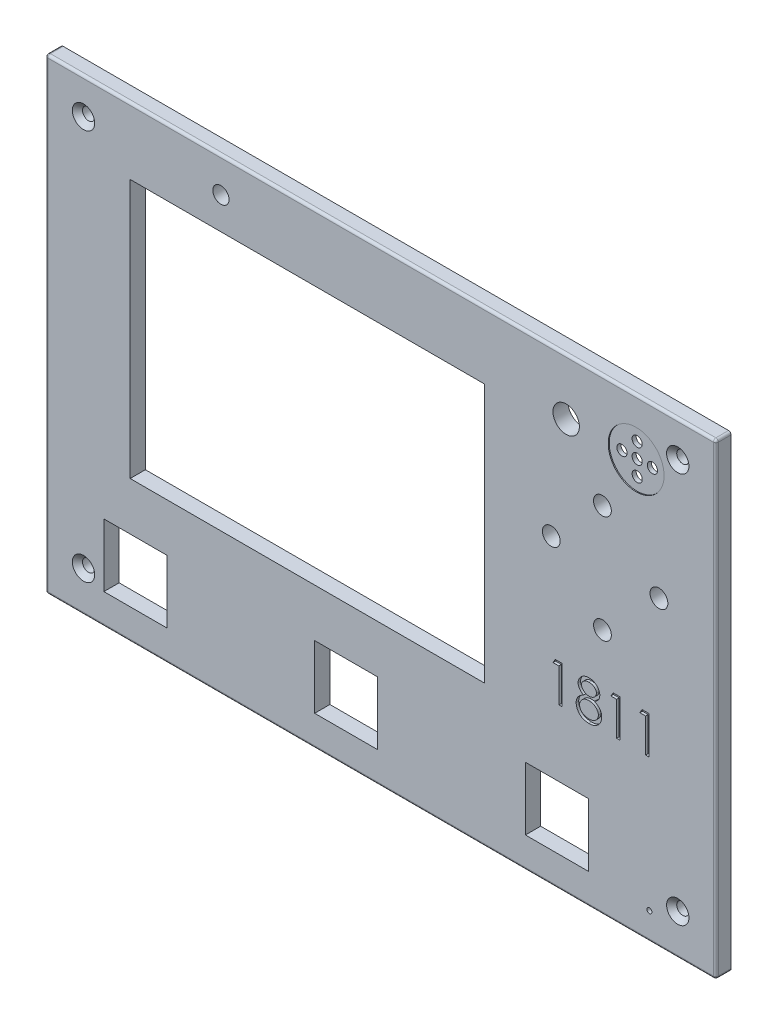
SolidWorks part; units mm, degrees
ref_plane "Plan de face" through (0, 0, 0) normal (0, 0, 1) x (1, 0, 0)
ref_plane "Plan de dessus" through (0, 0, 0) normal (0, 1, 0) x (1, 0, 0)
ref_plane "Plan de droite" through (0, 0, 0) normal (1, 0, 0) x (0, 0, -1)
sketch "Esquisse1" plane through (0, 0, 0) normal (0, 0, 1) x (1, 0, 0)
  line L1 (-52.1989, 55.8286) -> (79.8011, 55.8286)
  line L2 (-52.1989, 55.8286) -> (-52.1989, -36.1714)
  line L3 (-52.1989, -36.1714) -> (79.8011, -36.1714)
  line L4 (79.8011, 55.8286) -> (79.8011, -36.1714)
extrude "Boss.-Extru.1" add sketch "Esquisse1" along normal blind 3
sketch "Esquisse2" plane through (0, 0, 3) normal (0, 0, 1) x (1, 0, 0)
  line L0 (-52.1989, 55.8286) -> (-52.1989, -36.1714) construction
  line L1 (-35.5189, 42.7286) -> (34.2811, 42.7286)
  line L2 (-35.5189, 42.7286) -> (-35.5189, -8.2714)
  line L3 (-35.5189, -8.2714) -> (34.2811, -8.2714)
  line L4 (34.2811, 42.7286) -> (34.2811, -8.2714)
  line L5 (79.8011, 55.8286) -> (-52.1989, 55.8286) construction
  dimension "D1" = 16.68
  dimension "D2" = 13.1
extrude "Enlèv. mat.-Extru.1" cut sketch "Esquisse2" against normal blind 3
sketch "Esquisse3" plane through (0, 0, 3) normal (0, 0, 1) x (1, 0, 0)
  line L0 (-52.1989, 55.8286) -> (-52.1989, -36.1714) construction
  line L1 (-40.6889, -17.7414) -> (-28.2889, -17.7414)
  line L2 (-40.6889, -17.7414) -> (-40.6889, -30.1414)
  line L3 (-40.6889, -30.1414) -> (-28.2889, -30.1414)
  line L4 (-28.2889, -17.7414) -> (-28.2889, -30.1414)
  line L5 (-52.1989, -36.1714) -> (79.8011, -36.1714) construction
  dimension "D1" = 11.51
  dimension "D2" = 6.03
extrude "Enlèv. mat.-Extru.2" cut sketch "Esquisse3" against normal blind 3
sketch "Esquisse5" plane through (0, 0, 3) normal (0, 0, 1) x (1, 0, 0)
  line L1 (0.8111, -17.7414) -> (13.2111, -17.7414)
  line L2 (0.8111, -17.7414) -> (0.8111, -30.1414)
  line L3 (0.8111, -30.1414) -> (13.2111, -30.1414)
  line L4 (13.2111, -17.7414) -> (13.2111, -30.1414)
  line L5 (-52.1989, -36.1714) -> (79.8011, -36.1714) construction
  line L7 (-28.2889, -30.1414) -> (-28.2889, -17.7414) construction
  dimension "D1" = 29.1
  dimension "D2" = 6.03
extrude "Enlèv. mat.-Extru.3" cut sketch "Esquisse5" against normal blind 3
sketch "Esquisse6" plane through (0, 0, 3) normal (0, 0, 1) x (1, 0, 0)
  line L1 (42.3111, -17.7414) -> (54.7111, -17.7414)
  line L2 (42.3111, -17.7414) -> (42.3111, -30.1414)
  line L3 (42.3111, -30.1414) -> (54.7111, -30.1414)
  line L4 (54.7111, -17.7414) -> (54.7111, -30.1414)
  line L6 (-52.1989, -36.1714) -> (79.8011, -36.1714) construction
  line L7 (13.2111, -30.1414) -> (13.2111, -17.7414) construction
  dimension "D1" = 6.03
  dimension "D2" = 29.1
sketch "Esquisse7" plane through (0, 0, 3) normal (0, 0, 1) x (1, 0, 0)
  line L2 (79.8011, -36.1714) -> (79.8011, 55.8286) construction
  line L3 (79.8011, 55.8286) -> (-52.1989, 55.8286) construction
  circle A0 centre (57.4711, 12.3986) radius 1.75
  circle A1 centre (68.6011, 23.3686) radius 1.75
  circle A2 centre (57.4711, 33.5986) radius 1.75
  circle A3 centre (47.4011, 23.3686) radius 1.75
  dimension "D1" = 22.33
  dimension "D3" = 11.2
  dimension "D4" = 22.33
  dimension "D5" = 22.23
  dimension "D6" = 32.46
  dimension "D7" = 32.4
  dimension "D8" = 32.46
  dimension "D2" = 43.43
extrude "Enlèv. mat.-Extru.5" cut sketch "Esquisse7" against normal blind 3
extrude "Enlèv. mat.-Extru.6" cut sketch "Esquisse6" against normal blind 3 contours L2 L3 L4 L1
sketch "Esquisse8" plane through (0, 0, 3) normal (0, 0, 1) x (1, 0, 0)
  line L0 (79.8011, 55.8286) -> (-52.1989, 55.8286) construction
  line L1 (-52.1989, 55.8286) -> (-52.1989, -36.1714) construction
  circle A0 centre (-17.6489, 49.0186) radius 1.6
  dimension "D1" = 6.81
  dimension "D2" = 34.55
extrude "Enlèv. mat.-Extru.7" cut sketch "Esquisse8" against normal blind 3
sketch "Esquisse9" plane through (0, 0, 3) normal (0, 0, 1) x (1, 0, 0)
  line L1 (79.8011, 55.8286) -> (-52.1989, 55.8286) construction
  line L2 (79.8011, -36.1714) -> (79.8011, 55.8286) construction
  circle A0 centre (50.3311, 44.7686) radius 2.6
  dimension "D1" = 11.06
  dimension "D2" = 29.47
extrude "Enlèv. mat.-Extru.8" cut sketch "Esquisse9" against normal blind 3
sketch "Esquisse10" plane through (0, 0, 3) normal (0, 0, 1) x (1, 0, 0)
  line L0 (79.8011, 55.8286) -> (-52.1989, 55.8286) construction
  line L1 (79.8011, -36.1714) -> (79.8011, 55.8286) construction
  circle A0 centre (64.1111, 44.7686) radius 1
  circle A1 centre (64.1111, 47.7686) radius 1
  circle A2 centre (64.1111, 41.7686) radius 1
  circle A3 centre (61.1111, 44.7686) radius 1
  circle A4 centre (67.1111, 44.7686) radius 1
  dimension "D1" = 11.06
  dimension "D4" = 0
  dimension "D2" = 15.69
  dimension "D5" = 0
extrude "Enlèv. mat.-Extru.9" cut sketch "Esquisse10" against normal blind 3 and the other way through all
sketch "Esquisse12" plane through (0, 0, 3) normal (0, 0, 1) x (1, 0, 0)
  circle A2 centre (64.1111, 44.7686) radius 5
  circle A3 centre (64.1111, 44.7686) radius 5.5
extrude "Enlèv. mat.-Extru.10" cut sketch "Esquisse12" against normal blind 0.2 contours A3
sketch "Esquisse14" [suppressed] plane through (0, 0, 2) normal (0, 0, 1) x (1, 0, 0)
  circle A0 centre (64.1111, 44.7686) radius 5
fillet "Congé1" radius 0.5 1 edges at (-52.1989, 9.8286, 3)
fillet "Congé2" radius 0.5 3 edges at (-52.1989, -36.1714, 1.25) (-52.0524, -36.1714, 2.8536) (14.0511, -36.1714, 3)
fillet "Congé3" radius 0.5 3 edges at (79.8011, -36.1714, 1.25) (79.8011, -36.0249, 2.8536) (79.8011, 10.0786, 3)
fillet "Congé4" radius 0.5 5 edges at (79.8011, 55.8286, 1.25) (79.6547, 55.8286, 2.8536) (-52.1989, 55.8286, 1.25) (-52.0524, 55.8286, 2.8536) (13.8011, 55.8286, 3)
sketch "Esquisse15" plane through (0, 0, 3) normal (0, 0, 1) x (1, 0, 0)
  line L0 (-51.6989, 55.8286) -> (79.3011, 55.8286) construction
  line L1 (-52.1989, -35.6714) -> (-52.1989, 55.3286) construction
  line L2 (79.8011, 55.3286) -> (79.8011, -35.6714) construction
  line L3 (79.3011, -36.1714) -> (-51.6989, -36.1714) construction
  circle A0 centre (-44.6989, 48.8286) radius 1.15
  circle A1 centre (72.3011, 48.8286) radius 1.15
  circle A2 centre (-44.6989, -28.1714) radius 1.15
  circle A3 centre (72.3011, -28.1714) radius 1.15
  dimension "D1" = 7
  dimension "D3" = 7
  dimension "D5" = 7.5
  dimension "D7" = 8
  dimension "D2" = 7.5
  dimension "D4" = 7.5
  dimension "D6" = 8
  dimension "D8" = 7.5
extrude "Enlèv. mat.-Extru.11" cut sketch "Esquisse15" against normal blind 3
sketch "Esquisse20" plane through (0, 0, 3) normal (0, 0, 1) x (1, 0, 0)
  line L0 (79.8011, 55.3286) -> (79.8011, -35.6714) construction
  line L1 (79.3011, -36.1714) -> (-51.6989, -36.1714) construction
  circle A0 centre (66.7111, -30.8414) radius 0.5
  dimension "D1" = 13.09
  dimension "D2" = 5.33
extrude "Enlèv. mat.-Extru.12" cut sketch "Esquisse20" against normal blind 3
hole_wizard "Fraisage pour vis à tête fraisée M23" positions "Esquisse21" profile "Esquisse22" countersink size "M2" standard "Ansi Metric" end condition through all
sketch "Esquisse21" plane through (0, 0, 3) normal (0, 0, 1) x (1, 0, 0)
  point P0 (72.3011, 48.8286)
  point P3 (-44.6989, 48.8286)
  point P6 (-44.6989, -28.1714)
  point P9 (72.3011, -28.1714)
sketch "Esquisse22" plane through (72.3011, 48.8286, 3) normal (1, 0, 0) x (0, -1, 0)
  line L0 (0, 0) -> (0, 3)
  line L1 (0, 3) -> (1.2, 3)
  line L2 (1.2, 3) -> (1.2, 1)
  line L3 (1.2, 1) -> (2.2, 0)
  line L5 (2.2, 0) -> (0, 0)
  line L6 (-1.2, 1) -> (-2.2, 0) construction
  line L11 (0, -6.35) -> (0, 107.95) construction
  dimension "Diamètre du perçage jusqu'au prochain" = 2.4
  dimension "Profondeur du perçage jusqu'au prochain" = 3
  dimension "Diamètre du fraisage entrant" = 4.4
  dimension "Angle du fraisage entrant" = 90
sketch "Esquisse23" plane through (0, 0, 0) normal (0, 0, -1) x (-1, 0, 0)
  circle A0 centre (-64.1111, 44.7686) radius 6.5
extrude "Enlèv. mat.-Extru.13" cut sketch "Esquisse23" against normal blind 2
sketch "Esquisse24" plane through (0, 0, 3) normal (0, 0, 1) x (1, 0, 0)
  text T0 "1811" font "Century Gothic" height in points 28
extrude "Enlèv. mat.-Extru.17" cut sketch "Esquisse24" against normal blind 0.5
